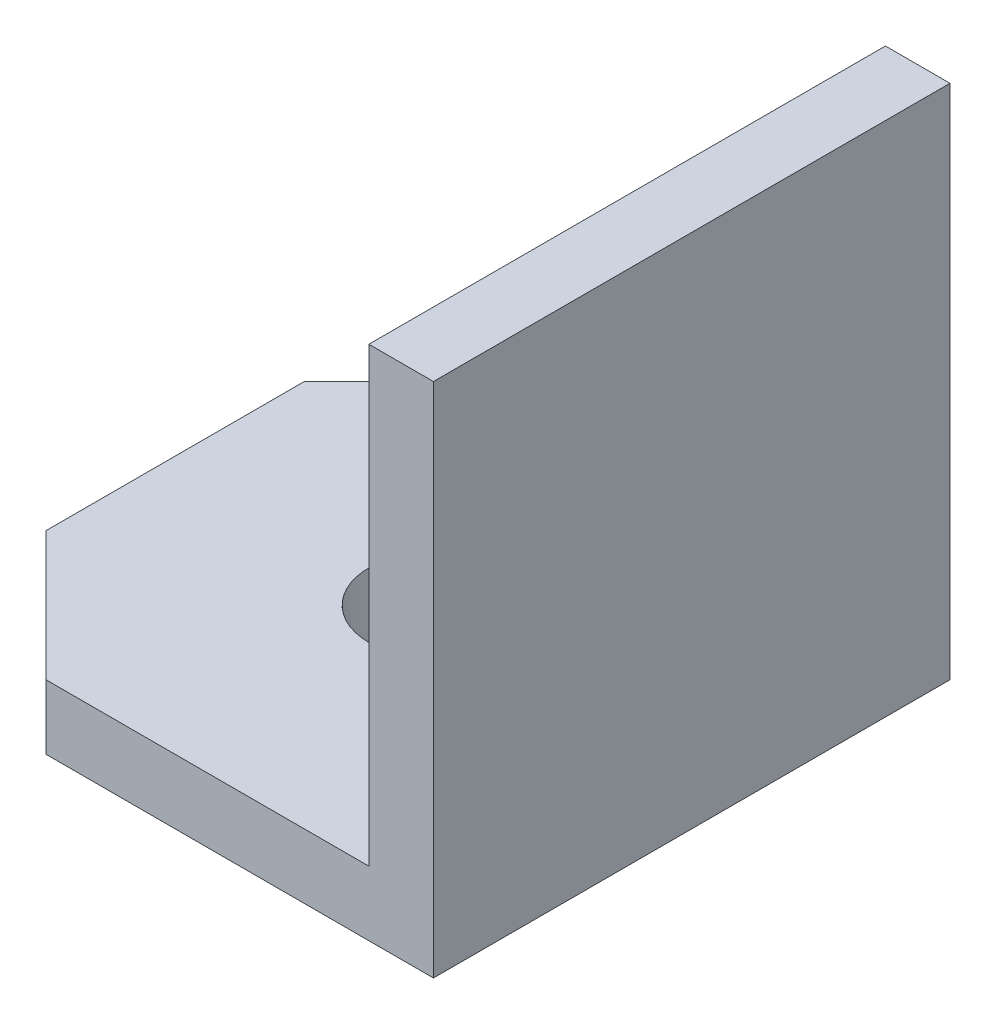
SolidWorks part; units mm, degrees
ref_plane "Front" through (0, 0, 0) normal (0, 0, 1) x (1, 0, 0)
ref_plane "Top" through (0, 0, 0) normal (0, 1, 0) x (1, 0, 0)
ref_plane "Right" through (0, 0, 0) normal (1, 0, 0) x (0, 0, -1)
sketch "Sketch1" plane through (0, 0, 0) normal (0, 0, 1) x (1, 0, 0)
  line L0 (-40, 0) -> (0, 0)
  line L1 (0, 0) -> (0, 40)
  dimension "D1" = 40
  dimension "D2" = 40
extrude "Extrude-Thin1" add sketch "Sketch1" along normal blind 40 thin thin type one direction reverse wall 5
chamfer "Chamfer1" distance 10 angle 45 2 edges at (-40, 2.5, 40) (-40, 2.5, 0)
sketch "Sketch2" plane through (0, 5, 0) normal (0, 1, 0) x (1, 0, 0)
  line L0 (-30, 0) -> (-5, 0) construction
  line L1 (-40, -30) -> (-40, -10) construction
  circle A0 centre (-20, -20) radius 5
  dimension "D1" = 10
  dimension "D2" = 20
  dimension "D3" = 20
extrude "Cut-Extrude1" cut sketch "Sketch2" against normal blind 10
